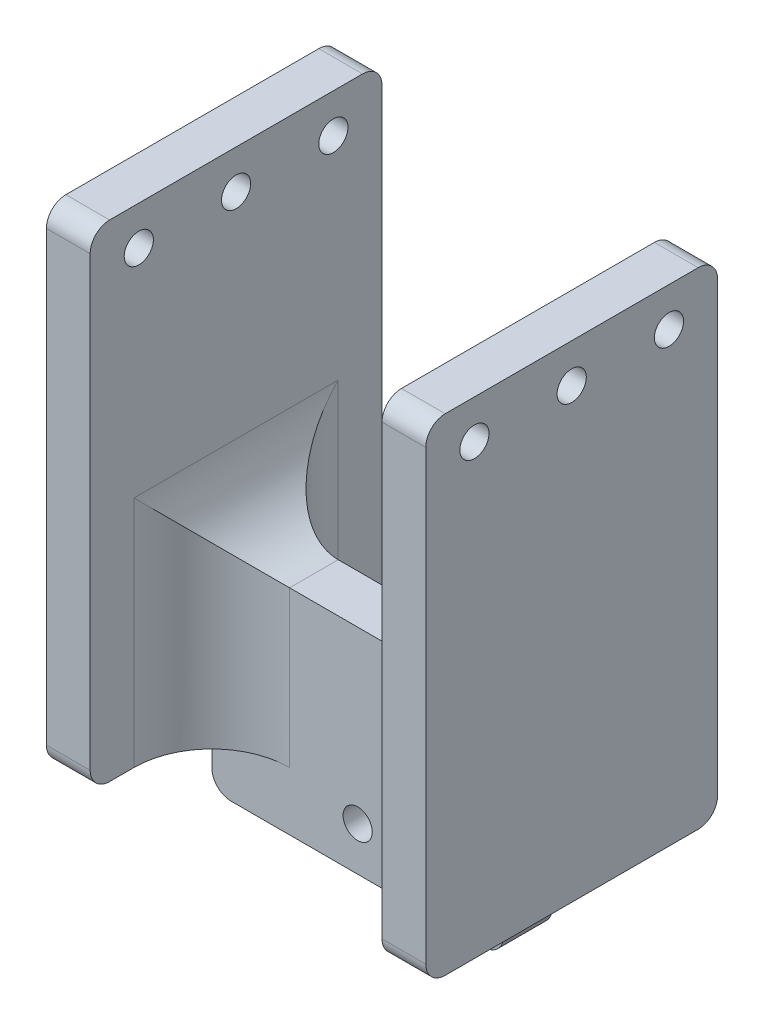
SolidWorks part; units mm, degrees
ref_plane "前视基准面" through (0, 0, 0) normal (0, 0, 1) x (1, 0, 0)
ref_plane "上视基准面" through (0, 0, 0) normal (0, 1, 0) x (1, 0, 0)
ref_plane "右视基准面" through (0, 0, 0) normal (1, 0, 0) x (0, 0, -1)
sketch "草图1" plane through (0, 0, 0) normal (0, 0, 1) x (1, 0, 0)
  line L1 (15, -25) -> (-15, -25)
  line L2 (15, -25) -> (15, 25)
  line L3 (15, 25) -> (-15, 25)
  line L4 (-15, -25) -> (-15, 25)
  line L5 (15, -25) -> (-15, 25) construction
  line L6 (15, 25) -> (-15, -25) construction
  point P0 (0, 0)
  dimension "D1" = 30
  dimension "D2" = 50
extrude "凸台-拉伸1" add sketch "草图1" along normal blind 5
sketch "草图5" plane through (-15, 0, 0) normal (-1, 0, 0) x (0, 0, 1)
  line L0 (5, 25) -> (0, 25) construction
  line L1 (17.5, 9) -> (-12.5, 9)
  line L2 (17.5, 9) -> (17.5, 59)
  line L3 (17.5, 59) -> (-12.5, 59)
  line L4 (-12.5, 9) -> (-12.5, 59)
  line L5 (17.5, 9) -> (-12.5, 59) construction
  line L6 (17.5, 59) -> (-12.5, 9) construction
  line L7 (2.5, -25) -> (2.5, 25) construction
  line L8 (5, -25) -> (0, -25) construction
  line L9 (2.5, 25) -> (2.5, 40.0267) construction
  point P0 (2.5, 34)
  point P7 (2.5, 24)
  dimension "D1" = 16
  dimension "D2" = 30
  dimension "D3" = 50
extrude "凸台-拉伸2" add sketch "草图5" along normal blind 4.5
mirror "镜向1" about plane through (0, 0, 0) normal (1, 0, 0) of "凸台-拉伸2"
sketch "草图6" plane through (-19.5, 0, 0) normal (-1, 0, 0) x (0, 0, 1)
  line L0 (2.5, 59) -> (2.5, 55) construction
  line L1 (17.5, 59) -> (-12.5, 59) construction
  circle A0 centre (2.5, 55) radius 1.5
  dimension "D1" = 4
  dimension "D2" = 3
extrude "切除-拉伸1" cut sketch "草图6" against normal through all
sketch "草图7" plane through (-19.5, 0, 0) normal (-1, 0, 0) x (0, 0, 1)
  line L0 (2.5, 55) -> (-7.5, 55) construction
  line L1 (2.5, 55) -> (12.5, 55) construction
  circle A0 centre (-7.5, 55) radius 1.5
  circle A1 centre (12.5, 55) radius 1.5
  dimension "D3" = 3
  dimension "D4" = 3
  dimension "D1" = 10
  dimension "D2" = 10
extrude "切除-拉伸2" cut sketch "草图7" against normal through all
sketch "草图9" plane through (0, 0, 5) normal (0, 0, 1) x (1, 0, 0)
  line L0 (0, -25) -> (0, -19) construction
  line L1 (-15, -25) -> (15, -25) construction
  circle A0 centre (0, -19) radius 1.5
  dimension "D2" = 3
  dimension "D1" = 6
sketch "草图10" plane through (0, 0, 0) normal (0, 0, -1) x (-1, 0, 0)
  line L0 (0, -13.5) -> (0, 7.5) construction
  circle A0 centre (0, -13.5) radius 1.5
  circle A1 centre (0, 7.5) radius 1.5
  dimension "D1" = 3
  dimension "D2" = 3
  dimension "D3" = 21
extrude "切除-拉伸3" cut sketch "草图10" against normal through all
sketch "草图11" plane through (0, 0, 0) normal (0, 0, -1) x (-1, 0, 0)
  line L0 (-15, -25) -> (-15, 9) construction
  line L1 (15, -25) -> (-15, -25)
  line L2 (15, -25) -> (15, 3)
  line L3 (15, 3) -> (-15, 3)
  line L4 (-15, -25) -> (-15, 3)
  dimension "D1" = 28
extrude "切除-拉伸4" cut sketch "草图11" against normal through all
fillet "圆角1" radius 8 4 edges at (-15, 17, 5) (15, 17, 5) (15, 17, 0) (-15, 17, 0)
fillet "圆角2" radius 8 2 edges at (-15, 25, 2.5) (15, 25, 2.5)
fillet "圆角3" radius 2 10 edges at (17.25, 9, -12.5) (-17.25, 9, -12.5) (17.25, 9, 17.5) (-17.25, 9, 17.5) (-17.25, 59, 17.5) (17.25, 59, 17.5) (17.25, 59, -12.5) (-17.25, 59, -12.5) (-15, 3, 2.5) (15, 3, 2.5)
